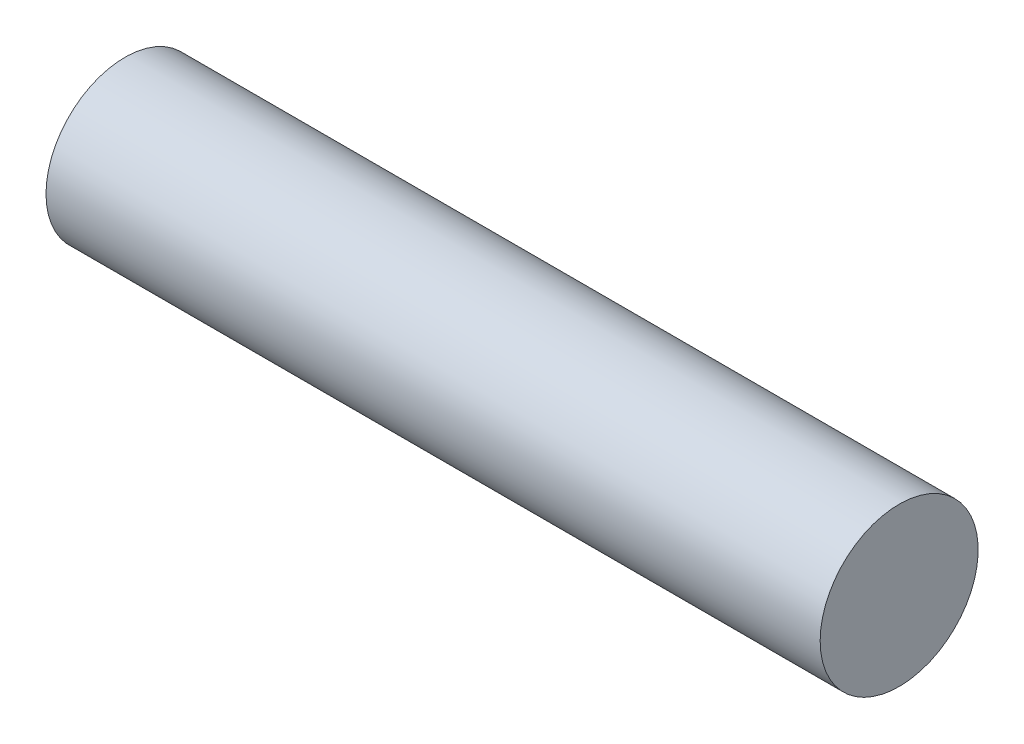
SolidWorks part; units mm, degrees
ref_plane "Plano frontal" through (0, 0, 0) normal (0, 0, 1) x (1, 0, 0)
ref_plane "Plano superior" through (0, 0, 0) normal (0, 1, 0) x (1, 0, 0)
ref_plane "Plano direito" through (0, 0, 0) normal (1, 0, 0) x (0, 0, -1)
sketch "Esboço1" plane through (0, 0, 0) normal (0, 0, 1) x (1, 0, 0)
  line L0 (0, 0) -> (49, 0)
  line L1 (49, 0) -> (49, 5)
  line L6 (49, 5) -> (0, 5)
  line L11 (0, 5) -> (0, 0)
  dimension "D1" = 5
  dimension "D9" = 49
revolve "Revolução1" add sketch "Esboço1" angle 360 about L0
